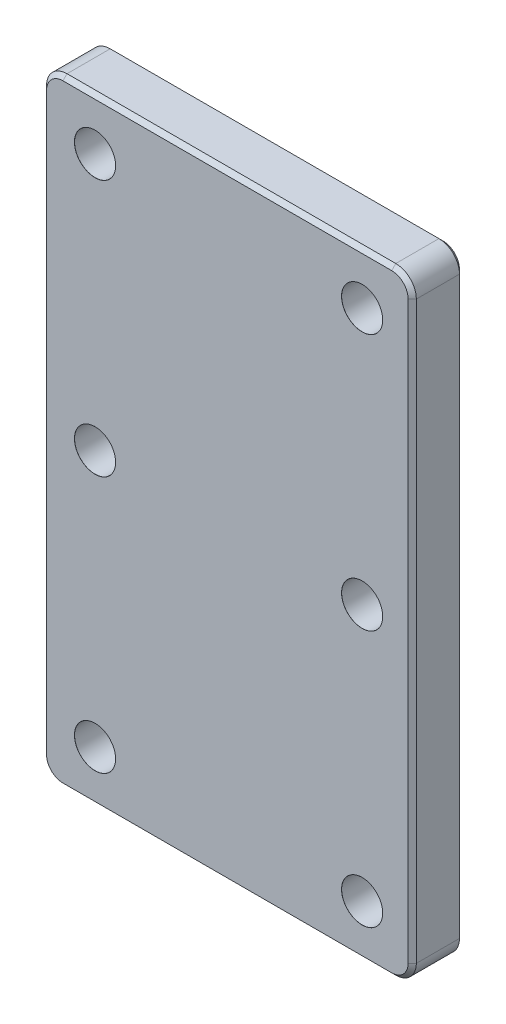
SolidWorks part; units mm, degrees
ref_plane "Front Plane" through (0, 0, 0) normal (1, 0, 0) x (0, 1, 0)
ref_plane "Top Plane" through (0, 0, 0) normal (0, 0, 1) x (0, 1, 0)
ref_plane "Right Plane" through (0, 0, 0) normal (0, 1, 0) x (-1, 0, 0)
sketch "Sketch2" plane through (0, 0, 0) normal (0, 0, 1) x (0, 1, 0)
  line L1 (-140, -90) -> (140, -90)
  line L2 (-150, -80) -> (-150, 80)
  line L3 (-140, 90) -> (140, 90)
  line L4 (150, -80) -> (150, 80)
  line L5 (-150, -90) -> (150, 90) construction
  line L6 (-150, 90) -> (150, -90) construction
  arc A0 (-140, -90) -> (-150, -80) centre (-140, -80) cw
  arc A1 (140, -90) -> (150, -80) centre (140, -80) ccw
  arc A2 (140, 90) -> (150, 80) centre (140, 80) cw
  arc A3 (-150, 80) -> (-140, 90) centre (-140, 80) cw
  point P0 (0, 0)
  dimension "D3" = 10
  dimension "D1" = 300
  dimension "D2" = 180
extrude "Boss-Extrude1" add sketch "Sketch2" along normal mid plane 25
sketch "Sketch3" plane through (0, 0, 12.5) normal (0, 0, 1) x (1, 0, 0)
  line L0 (-64.3834, -125) -> (-64.3834, 0) construction
  line L1 (-64.3834, 0) -> (-64.3834, 125) construction
  line L2 (-64.3834, 125) -> (65.6166, 125) construction
  line L3 (65.6166, 125) -> (65.6166, 0) construction
  line L4 (65.6166, 0) -> (65.6166, -125) construction
  line L5 (65.6166, -125) -> (-64.3834, -125) construction
  dimension "D1" = 250
  dimension "D2" = 130
hole_wizard "Ø20.0 (20) Diameter Hole1" positions "3DSketch1" profile "Sketch4" hole size "Ø20.0" standard "ISO" end condition through all
sketch3d "3DSketch1"
  point P0 (-64.3834, -125, 12.5)
  point P3 (-64.3834, 0, 12.5)
  point P6 (-64.3834, 125, 12.5)
  point P9 (65.6166, 125, 12.5)
  point P12 (65.6166, 0, 12.5)
  point P15 (65.6166, -125, 12.5)
sketch "Sketch4" plane through (-64.3834, -125, 12.5) normal (1, 0, 0) x (0, -1, 0)
  line L0 (0, 0) -> (0, 25)
  line L1 (0, 25) -> (10, 25)
  line L2 (10, 25) -> (10, 0.025)
  line L3 (10, 0.025) -> (10.025, 0)
  line L5 (10.025, 0) -> (0, 0)
  line L6 (-10, 0.025) -> (-10.025, 0) construction
  line L11 (0, -6.35) -> (0, 107.95) construction
  dimension "Thru Hole Dia." = 20
  dimension "Thru Hole Depth" = 25
  dimension "Near C'Sink Dia." = 20.05
  dimension "Near C'Sink Angle" = 90
chamfer "Chamfer2" distance 2 angle 45 8 edges at (-90, 0, 12.5) (-87.0711, -147.0711, 12.5) (-87.0711, 147.0711, 12.5) (0, -150, 12.5) (0, 150, 12.5) (87.0711, -147.0711, 12.5) (87.0711, 147.0711, 12.5) (90, 0, 12.5)
chamfer "Chamfer3" distance 2 angle 45 14 edges at (90, 0, -12.5) (87.0711, 147.0711, -12.5) (0, 150, -12.5) (-87.0711, 147.0711, -12.5) (-90, 0, -12.5) (-87.0711, -147.0711, -12.5) (0, -150, -12.5) (87.0711, -147.0711, -12.5) (75.6166, -125, -12.5) (75.6166, 0, -12.5) (75.6166, 125, -12.5) (-54.3834, 125, -12.5) (-54.3834, 0, -12.5) (-54.3834, -125, -12.5)
